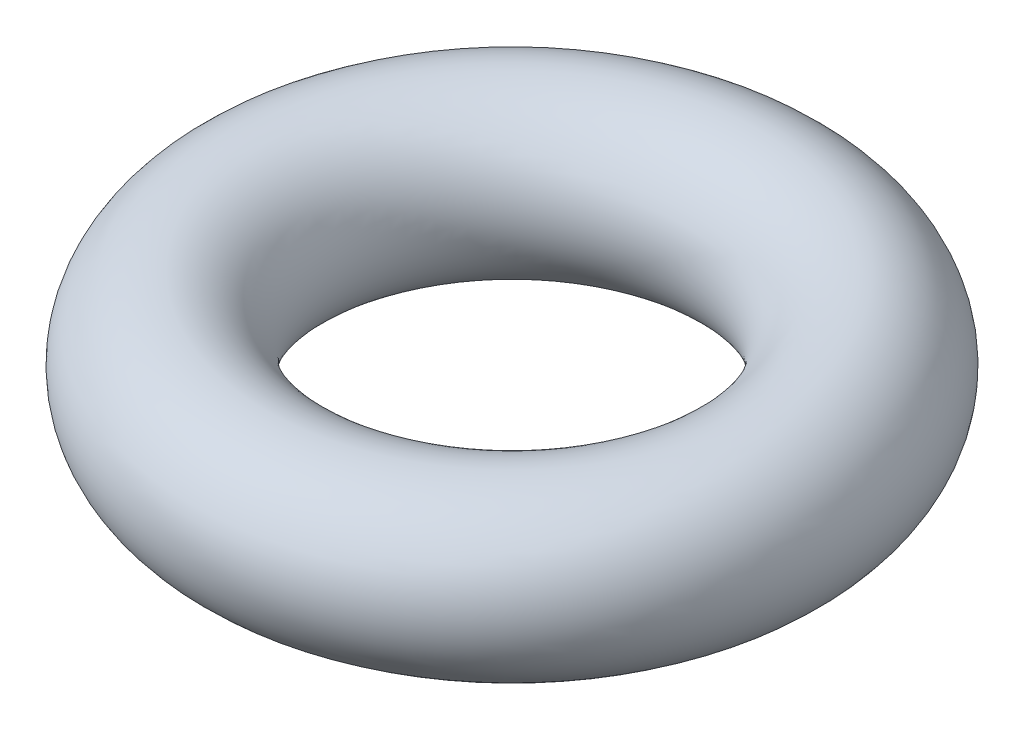
SolidWorks part; units mm, degrees
material "Rubber"
ref_plane "Front Plane" through (0, 0, 0) normal (0, 0, 1) x (1, 0, 0)
ref_plane "Top Plane" through (0, 0, 0) normal (0, 1, 0) x (1, 0, 0)
ref_plane "Right Plane" through (0, 0, 0) normal (1, 0, 0) x (0, 0, -1)
sketch "Sketch1" plane through (0, 0, 0) normal (0, 0, 1) x (1, 0, 0)
  line L0 (0, -24.5642) -> (0, 1205.2897) construction
  circle A0 centre (2.3876, 0) radius 0.7938
  dimension "D1" = 1.5875
  dimension "D2" = 2.3876
revolve "Revolve1" add sketch "Sketch1" angle 360 about L0
ref_plane "Plane1" through (0, 0.762, 0) normal (0, 1, 0) x (1, 0, 0)
ref_plane "Plane2" through (0, -0.762, 0) normal (0, 1, 0) x (1, 0, 0)
